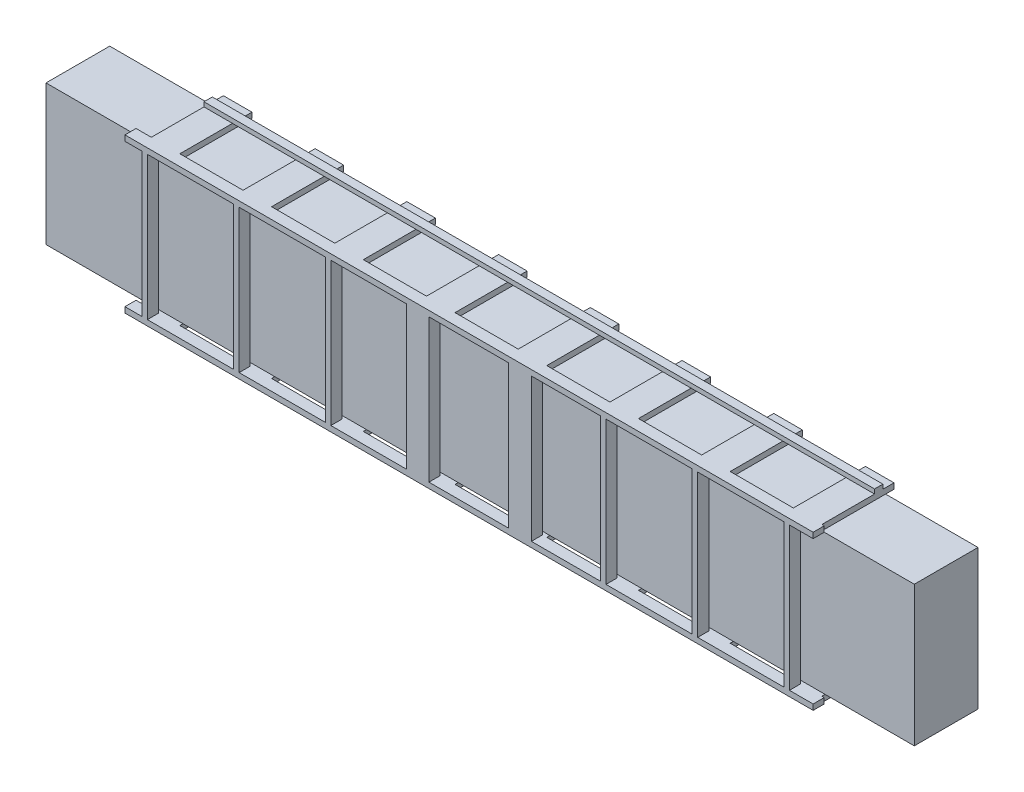
SolidWorks part; units mm, degrees
ref_plane "Front Plane" through (0, 0, 0) normal (0, 0, 1) x (1, 0, 0)
ref_plane "Top Plane" through (0, 0, 0) normal (0, 1, 0) x (1, 0, 0)
ref_plane "Right Plane" through (0, 0, 0) normal (1, 0, 0) x (0, 0, -1)
sketch "Sketch1" plane through (0, 0, 0) normal (0, 0, 1) x (1, 0, 0)
  line L0 (0, 1388) -> (6190, 1388)
  line L1 (0, 50) -> (6190, 50)
  line L2 (0, 50) -> (0, 0)
  line L3 (0, 0) -> (6190, 0)
  line L4 (6190, 50) -> (6190, 0)
  line L5 (0, 1388) -> (0, 1338)
  line L6 (0, 1338) -> (6190, 1338)
  line L7 (6190, 1388) -> (6190, 1338)
  dimension "D1" = 1288
  dimension "D2" = 50
extrude "Boss-Extrude1" add sketch "Sketch1" along normal blind 100
sketch "Sketch2" plane through (0, 0, 0) normal (0, -1, 0) x (1, 0, 0)
  line L0 (0, 100) -> (6190, 100) construction
  line L1 (2534, 100) -> (2734, 100)
  line L2 (2534, 100) -> (2534, 0)
  line L3 (2534, 0) -> (2734, 0)
  line L4 (2734, 100) -> (2734, 0)
  line L5 (0, 0) -> (6190, 0) construction
  line L6 (0, 100) -> (0, 0) construction
  line L8 (3456, 100) -> (3656, 100)
  line L9 (3456, 100) -> (3456, 0)
  line L10 (3456, 0) -> (3656, 0)
  line L11 (3656, 100) -> (3656, 0)
  point P8 (0, 50)
  dimension "D1" = 200
  dimension "D2" = 2534
  dimension "D3" = 2534
  dimension "D4" = 200
extrude "Boss-Extrude2" add sketch "Sketch2" against normal up to surface (1388 mm away) up to face at (3095, 1388, 50)
sketch "Sketch4" plane through (0, 50, 0) normal (0, 1, 0) x (1, 0, 0)
  line L0 (2534, 0) -> (0, 0) construction
  line L1 (152, 0) -> (202, 0)
  line L2 (152, 0) -> (152, -100)
  line L3 (152, -100) -> (202, -100)
  line L4 (202, 0) -> (202, -100)
  line L5 (2534, -100) -> (0, -100) construction
  line L6 (0, -100) -> (0, 0) construction
  line L7 (977, 0) -> (977, -100)
  line L8 (977, 0) -> (1027, 0)
  line L9 (1027, 0) -> (1027, -100)
  line L10 (977, -100) -> (1027, -100)
  line L11 (1802, 0) -> (1802, -100)
  line L12 (1802, 0) -> (1852, 0)
  line L13 (1852, 0) -> (1852, -100)
  line L14 (1802, -100) -> (1852, -100)
  line L15 (2627, 0) -> (2627, -100)
  line L16 (2627, 0) -> (2677, 0)
  line L17 (2677, 0) -> (2677, -100)
  line L18 (2627, -100) -> (2677, -100)
  line L19 (3452, 0) -> (3452, -100)
  line L20 (3452, 0) -> (3502, 0)
  line L21 (3502, 0) -> (3502, -100)
  line L22 (3452, -100) -> (3502, -100)
  line L23 (4277, 0) -> (4277, -100)
  line L24 (4277, 0) -> (4327, 0)
  line L25 (4327, 0) -> (4327, -100)
  line L26 (4277, -100) -> (4327, -100)
  line L27 (5102, 0) -> (5102, -100)
  line L28 (5102, 0) -> (5152, 0)
  line L29 (5152, 0) -> (5152, -100)
  line L30 (5102, -100) -> (5152, -100)
  line L31 (5927, 0) -> (5927, -100)
  line L32 (5927, 0) -> (5977, 0)
  line L33 (5977, 0) -> (5977, -100)
  line L34 (5927, -100) -> (5977, -100)
  dimension "D1" = 152
  dimension "D2" = 50
  dimension "D3" = 8
extrude "Boss-Extrude3" add sketch "Sketch4" along normal up to next (1288 mm away)
sketch "Sketch5" plane through (0, 0, 0) normal (0, 0, 1) x (1, 0, 0)
  line L0 (5912.4, 1388) -> (6169, 1388)
  line L1 (137.4, 1388) -> (137.4, 1338)
  line L2 (394, 50) -> (137.4, 50)
  line L3 (394, 1388) -> (394, 1338)
  line L4 (137.4, 1388) -> (394, 1388)
  line L5 (394, 1338) -> (137.4, 1338)
  line L6 (137.4, 0) -> (394, 0)
  line L7 (394, 0) -> (394, 50)
  line L8 (137.4, 0) -> (137.4, 50)
  line L9 (5912.4, 0) -> (5912.4, 50)
  line L10 (6169, 50) -> (5912.4, 50)
  line L11 (6169, 0) -> (6169, 50)
  line L12 (5087.4, 0) -> (5087.4, 50)
  line L13 (1219, 1388) -> (1219, 1338)
  line L14 (962.4, 1388) -> (1219, 1388)
  line L15 (1219, 1338) -> (962.4, 1338)
  line L16 (5344, 50) -> (5087.4, 50)
  line L17 (962.4, 1388) -> (962.4, 1338)
  line L18 (5087.4, 0) -> (5344, 0)
  line L19 (5344, 0) -> (5344, 50)
  line L20 (4262.4, 0) -> (4262.4, 50)
  line L21 (4519, 50) -> (4262.4, 50)
  line L22 (2044, 1388) -> (2044, 1338)
  line L23 (1787.4, 1388) -> (2044, 1388)
  line L24 (2044, 1338) -> (1787.4, 1338)
  line L25 (4262.4, 0) -> (4519, 0)
  line L26 (1787.4, 1388) -> (1787.4, 1338)
  line L27 (4519, 0) -> (4519, 50)
  line L28 (3437.4, 0) -> (3437.4, 50)
  line L29 (3694, 50) -> (3437.4, 50)
  line L30 (3437.4, 0) -> (3694, 0)
  line L31 (2869, 1388) -> (2869, 1338)
  line L32 (2612.4, 1388) -> (2869, 1388)
  line L33 (2869, 1338) -> (2612.4, 1338)
  line L34 (3694, 0) -> (3694, 50)
  line L35 (2612.4, 1388) -> (2612.4, 1338)
  line L36 (2612.4, 0) -> (2612.4, 50)
  line L37 (2869, 50) -> (2612.4, 50)
  line L38 (2612.4, 0) -> (2869, 0)
  line L39 (2869, 0) -> (2869, 50)
  line L40 (3694, 1388) -> (3694, 1338)
  line L41 (3437.4, 1388) -> (3694, 1388)
  line L42 (3694, 1338) -> (3437.4, 1338)
  line L43 (1787.4, 0) -> (1787.4, 50)
  line L44 (3437.4, 1388) -> (3437.4, 1338)
  line L45 (2044, 50) -> (1787.4, 50)
  line L46 (1787.4, 0) -> (2044, 0)
  line L47 (2044, 0) -> (2044, 50)
  line L48 (962.4, 0) -> (962.4, 50)
  line L49 (4519, 1388) -> (4519, 1338)
  line L50 (4262.4, 1388) -> (4519, 1388)
  line L51 (4519, 1338) -> (4262.4, 1338)
  line L52 (1219, 50) -> (962.4, 50)
  line L53 (4262.4, 1388) -> (4262.4, 1338)
  line L54 (962.4, 0) -> (1219, 0)
  line L55 (1219, 0) -> (1219, 50)
  line L56 (5912.4, 0) -> (6169, 0)
  line L58 (5344, 1388) -> (5344, 1338)
  line L59 (5087.4, 1388) -> (5344, 1388)
  line L60 (5344, 1338) -> (5087.4, 1338)
  line L62 (5087.4, 1388) -> (5087.4, 1338)
  line L67 (6169, 1388) -> (6169, 1338)
  line L69 (6169, 1338) -> (5912.4, 1338)
  line L71 (5912.4, 1388) -> (5912.4, 1338)
  line L73 (152, 694) -> (5977, 694) construction
  line L74 (152, 1338) -> (152, 50) construction
  line L75 (5977, 1338) -> (5977, 50) construction
  line L148 (137.4, 1388) -> (137.4, 1338) [skipped]
  line L149 (140.4, 1385.8) -> (140.4, 1338) [skipped]
  line L150 (140.4, 1338) -> (137.4, 1338) [skipped]
  line L151 (152, 1338) -> (137.4, 1338) construction
  line L152 (137.4, 1388) -> (140.4, 1385.8) [skipped]
  line L153 (965.4, 1385.8) -> (965.4, 1338) [skipped]
  line L154 (962.4, 1388) -> (965.4, 1385.8) [skipped]
  line L155 (965.4, 1338) -> (962.4, 1338) [skipped]
  line L156 (977, 1338) -> (962.4, 1338) construction
  line L157 (1787.4, 1388) -> (1790.4, 1385.8) [skipped]
  line L158 (1790.4, 1385.8) -> (1790.4, 1338) [skipped]
  line L159 (1790.4, 1338) -> (1787.4, 1338) [skipped]
  line L160 (1802, 1338) -> (1787.4, 1338) construction
  line L161 (2612.4, 1388) -> (2615.4, 1385.8) [skipped]
  line L162 (2615.4, 1338) -> (2612.4, 1338) [skipped]
  line L163 (2627, 1338) -> (2612.4, 1338) construction
  line L164 (2615.4, 1385.8) -> (2615.4, 1338) [skipped]
  line L165 (3437.4, 1388) -> (3440.4, 1385.8) [skipped]
  line L166 (3440.4, 1338) -> (3437.4, 1338) [skipped]
  line L167 (3452, 1338) -> (3437.4, 1338) construction
  line L168 (3440.4, 1385.8) -> (3440.4, 1338) [skipped]
  line L169 (4262.4, 1388) -> (4265.4, 1385.8) [skipped]
  line L170 (4265.4, 1338) -> (4262.4, 1338) [skipped]
  line L171 (4277, 1338) -> (4262.4, 1338) construction
  line L172 (4265.4, 1385.8) -> (4265.4, 1338) [skipped]
  line L173 (5087.4, 1388) -> (5090.4, 1385.8) [skipped]
  line L174 (5090.4, 1338) -> (5087.4, 1338) [skipped]
  line L175 (5102, 1338) -> (5087.4, 1338) construction
  line L176 (5090.4, 1385.8) -> (5090.4, 1338) [skipped]
  line L177 (5912.4, 1388) -> (5915.4, 1385.8) [skipped]
  line L178 (5912.4, 1388) -> (6169, 1388) [skipped]
  line L179 (5915.4, 1338) -> (5912.4, 1338) [skipped]
  line L180 (5927, 1338) -> (5912.4, 1338) construction
  line L181 (5915.4, 1385.8) -> (5915.4, 1338) [skipped]
  line L182 (5912.4, 1388) -> (5912.4, 1338) [skipped]
  line L183 (5087.4, 1388) -> (5087.4, 1338) [skipped]
  line L184 (4262.4, 1388) -> (4262.4, 1338) [skipped]
  line L185 (3437.4, 1388) -> (3437.4, 1338) [skipped]
  line L186 (2612.4, 1388) -> (2612.4, 1338) [skipped]
  line L187 (1787.4, 1388) -> (1787.4, 1338) [skipped]
  line L188 (962.4, 1388) -> (962.4, 1338) [skipped]
  line L189 (137.4, 1388) -> (137.4, 1338) [skipped]
  dimension "D2" = 50
  dimension "D3" = 8
extrude "Boss-Extrude4" add sketch "Sketch5" against normal blind 648.4
sketch "Sketch11" plane through (0, 0, 0) normal (1, 0, 0) x (0, 0, -1)
  line L1 (0, 1338) -> (572.9754, 1338)
  line L2 (0, 1338) -> (0, 78.6868)
  line L3 (0, 78.6868) -> (572.9754, 78.6868)
  line L4 (572.9754, 1338) -> (572.9754, 78.6868)
sketch "Sketch13" plane through (6169, 0, 0) normal (1, 0, 0) x (0, 0, -1)
  line L0 (548.4, 0) -> (473.4, 0)
  line L1 (548.4, 0) -> (548.4, -40)
  line L2 (548.4, -40) -> (473.4, -40)
  line L3 (473.4, 0) -> (473.4, -40)
  line L4 (548.4, 1388) -> (473.4, 1388)
  line L5 (548.4, 1388) -> (548.4, 1428)
  line L6 (548.4, 1428) -> (473.4, 1428)
  line L7 (473.4, 1388) -> (473.4, 1428)
  line L13 (648.4, 0) -> (648.4, 50) construction
  line L14 (648.4, 0) -> (0, 0) construction
  line L15 (648.4, 1388) -> (0, 1388) construction
  dimension "D1" = 75
  dimension "D2" = 40
  dimension "D3" = 40
  dimension "D4" = 75
  dimension "D6" = 100
  dimension "D7" = 0
  dimension "D8" = 0
extrude "Boss-Extrude12" add sketch "Sketch13" against normal up to surface (6031.6 mm away) up to face at (137.4, 1363, -324.2)
extrude "Boss-Extrude10" add sketch "Sketch11" along normal blind 7000 separate body
sketch "Sketch12" plane through (0, 0, 0) normal (-1, 0, 0) x (0, 0, 1)
  line L1 (-572.9754, 78.6868) -> (0, 78.6868)
  line L2 (-572.9754, 78.6868) -> (-572.9754, 1338)
  line L3 (-572.9754, 1338) -> (0, 1338)
  line L4 (0, 78.6868) -> (0, 1338)
extrude "Boss-Extrude11" add sketch "Sketch12" along normal blind 810
